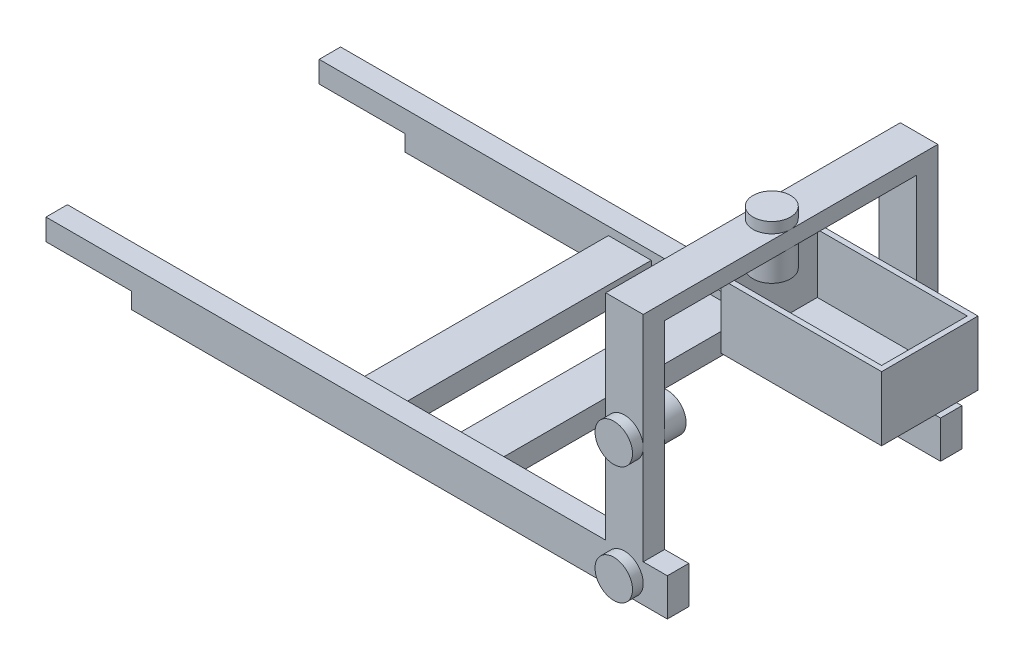
SolidWorks part; units mm, degrees
ref_plane "Front Plane" through (0, 0, 0) normal (0, 0, 1) x (1, 0, 0)
ref_plane "Top Plane" through (0, 0, 0) normal (0, 1, 0) x (1, 0, 0)
ref_plane "Right Plane" through (0, 0, 0) normal (1, 0, 0) x (0, 0, -1)
sketch "Sketch1" plane through (0, 0, 0) normal (0, 0, 1) x (1, 0, 0)
  line L0 (0, 0) -> (1473.2, 0)
  line L1 (0, 0) -> (0, -50.8)
  line L2 (0, -50.8) -> (203.2, -50.8)
  line L3 (203.2, -50.8) -> (203.2, -88.9)
  line L4 (203.2, -88.9) -> (1473.2, -88.9)
  line L5 (1473.2, -88.9) -> (1473.2, 0)
  dimension "D1" = 1473.2
  dimension "D2" = 88.9
  dimension "D3" = 50.8
  dimension "D4" = 203.2
ref_plane "Plane1" through (0, 0, 596.9) normal (0, 0, 1) x (1, 0, 0)
sketch "Sketch4" plane through (0, 0, 596.9) normal (0, 0, 1) x (1, 0, 0)
  line L0 (0, 0) -> (1473.2, 0)
  line L1 (0, 0) -> (0, -50.8)
  line L2 (0, -50.8) -> (203.2, -50.8)
  line L3 (203.2, -50.8) -> (203.2, -88.9)
  line L4 (203.2, -88.9) -> (1473.2, -88.9)
  line L5 (1473.2, -88.9) -> (1473.2, 0)
  line L6 (0, 0) -> (1473.2, 0) construction
  line L7 (203.2, -88.9) -> (1473.2, -88.9) construction
  line L8 (0, -50.8) -> (203.2, -50.8) construction
extrude "Boss-Extrude1" add sketch "Sketch1" against normal blind 50.8
extrude "Boss-Extrude2" add sketch "Sketch4" along normal blind 50.8 separate body contours L0 L5 L4 L3 L2 L1
sketch "Sketch5" plane through (0, 0, 0) normal (0, 0, 1) x (1, 0, 0)
  line L0 (1016, -44.45) -> (1473.2, -44.45) construction
  line L1 (914.4, -19.05) -> (1016, -19.05)
  line L2 (914.4, -19.05) -> (914.4, -69.85)
  line L3 (914.4, -69.85) -> (1016, -69.85)
  line L4 (1016, -19.05) -> (1016, -69.85)
  line L5 (685.8, -19.05) -> (787.4, -19.05)
  line L6 (685.8, -19.05) -> (685.8, -69.85)
  line L7 (685.8, -69.85) -> (787.4, -69.85)
  line L8 (787.4, -19.05) -> (787.4, -69.85)
  line L9 (1473.2, -88.9) -> (1473.2, 0) construction
  line L10 (914.4, -44.45) -> (787.4, -44.45) construction
  dimension "D1" = 101.6
  dimension "D2" = 50.8
  dimension "D3" = 457.2
  dimension "D4" = 685.8
extrude "Boss-Extrude3" add sketch "Sketch5" along normal blind 596.9
sketch "Sketch6" plane through (0, 0, 647.7) normal (0, 0, 1) x (1, 0, 0)
  line L0 (0, 0) -> (1473.2, 0) construction
  line L1 (203.2, -88.9) -> (1473.2, -88.9) construction
  line L2 (1371.6, -44.45) -> (1473.2, -44.45) construction
  line L3 (1473.2, -88.9) -> (1473.2, 0) construction
  circle A0 centre (1371.6, -44.45) radius 44.45
  dimension "D1" = 101.6
extrude "Boss-Extrude4" add sketch "Sketch6" along normal blind 25.4
sketch "Sketch7" plane through (0, 0, 0) normal (0, 1, 0) x (1, 0, 0)
  line L0 (-48.895, -596.9) -> (48.895, -596.9) construction
  line L1 (1327.15, -596.9) -> (1416.05, -596.9)
  line L2 (1327.15, -596.9) -> (1327.15, -647.7)
  line L3 (1327.15, -647.7) -> (1416.05, -647.7)
  line L4 (1416.05, -596.9) -> (1416.05, -647.7)
  line L5 (0, -647.7) -> (1371.6, -647.7) construction
  line L6 (1473.2, 50.8) -> (0, 50.8) construction
  line L7 (1416.05, 50.8) -> (1327.15, 50.8)
  line L8 (1416.05, 50.8) -> (1416.05, 0)
  line L9 (1416.05, 0) -> (1327.15, 0)
  line L10 (1327.15, 50.8) -> (1327.15, 0)
  line L11 (1327.15, 0) -> (1371.6, 0) construction
  line L12 (1473.2, 0) -> (0, 0) construction
  dimension "D1" = 88.9
extrude "Boss-Extrude5" add sketch "Sketch7" along normal blind 508
sketch "Sketch8" plane through (0, 0, 0) normal (0, 0, 1) x (1, 0, 0)
  line L0 (1416.05, 508) -> (1416.05, 0) construction
  line L1 (1327.15, 508) -> (1416.05, 508)
  line L2 (1327.15, 508) -> (1327.15, 469.9)
  line L3 (1327.15, 469.9) -> (1416.05, 469.9)
  line L4 (1416.05, 508) -> (1416.05, 469.9)
  dimension "D1" = 38.1
extrude "Boss-Extrude6" add sketch "Sketch8" along normal blind 596.9
sketch "Sketch10" plane through (0, 0, 0) normal (0, 0, 1) x (1, 0, 0)
  line L0 (1473.2, 0) -> (1172.4205, 0) construction
  line L1 (1181.1, 254) -> (1562.1, 254)
  line L2 (1181.1, 254) -> (1181.1, 101.6)
  line L3 (1181.1, 101.6) -> (1562.1, 101.6)
  line L4 (1562.1, 254) -> (1562.1, 101.6)
  line L5 (1327.15, 0) -> (0, 0) construction
  line L6 (1371.6, 0) -> (1371.6, 508) construction
  line L7 (1416.05, 508) -> (1327.15, 508) construction
  point P14 (1371.6, 508)
  point P15 (1371.6, 254)
  dimension "D1" = 101.6
  dimension "D2" = 152.4
  dimension "D3" = 381
extrude "Boss-Extrude7" add sketch "Sketch10" along normal blind 228.6
sketch "Sketch11" plane through (0, 254, 0) normal (0, 1, 0) x (1, 0, 0)
  line L12 (1549.4, -12.7) -> (1416.05, -12.7)
  line L13 (1416.05, -12.7) -> (1327.15, -12.7)
  line L14 (1327.15, -12.7) -> (1193.8, -12.7)
  line L15 (1193.8, -12.7) -> (1193.8, -215.9)
  line L16 (1193.8, -215.9) -> (1549.4, -215.9)
  line L17 (1549.4, -215.9) -> (1549.4, -12.7)
  line L18 (1549.4, -12.7) -> (1416.05, -12.7)
  line L19 (1416.05, -12.7) -> (1327.15, -12.7)
  line L20 (1327.15, -12.7) -> (1193.8, -12.7)
  line L21 (1193.8, -12.7) -> (1193.8, -215.9)
  line L22 (1193.8, -215.9) -> (1549.4, -215.9)
  line L23 (1549.4, -215.9) -> (1549.4, -12.7)
  dimension "D1" = 12.7
extrude "Cut-Extrude1" cut sketch "Sketch11" against normal blind 139.7
sketch "Sketch13" plane through (0, 508, 0) normal (0, 1, 0) x (1, 0, 0)
  line L0 (1327.15, 50.8) -> (1327.15, -647.7) construction
  line L1 (1416.05, -647.7) -> (1416.05, 50.8) construction
  circle A0 centre (1371.6, -298.45) radius 44.45
  point P5 (1327.15, -298.45)
extrude "Boss-Extrude8" add sketch "Sketch13" along normal blind 25.4 and the other way blind 101.6
sketch "Sketch14" plane through (0, 0, 647.7) normal (0, 0, 1) x (1, 0, 0)
  line L0 (1371.6, 469.9) -> (1371.6, 0) construction
  line L1 (0, 0) -> (1327.15, 0) construction
  line L2 (1416.05, 508) -> (1416.05, 0) construction
  line L3 (1327.15, 469.9) -> (1416.05, 469.9) construction
  line L4 (1327.15, 508) -> (1327.15, 0) construction
  circle A0 centre (1371.6, 234.95) radius 44.45
  point P8 (1371.6, 234.95)
  point P22 (1371.6, 469.9)
extrude "Boss-Extrude9" add sketch "Sketch14" along normal blind 25.4 and the other way blind 101.6 contours A0
sketch "Sketch15" plane through (0, 0, -50.8) normal (0, 0, -1) x (-1, 0, 0)
  line L0 (-1371.6, -44.45) -> (-1200.8186, -44.45) construction
  line L1 (-1327.15, 508) -> (-1327.15, 0) construction
  line L2 (-203.2, -88.9) -> (-1473.2, -88.9) construction
  line L3 (-1473.2, 0) -> (-1416.05, 0) construction
  circle A0 centre (-1371.6, -44.45) radius 44.45
extrude "Boss-Extrude10" add sketch "Sketch15" along normal blind 25.4
